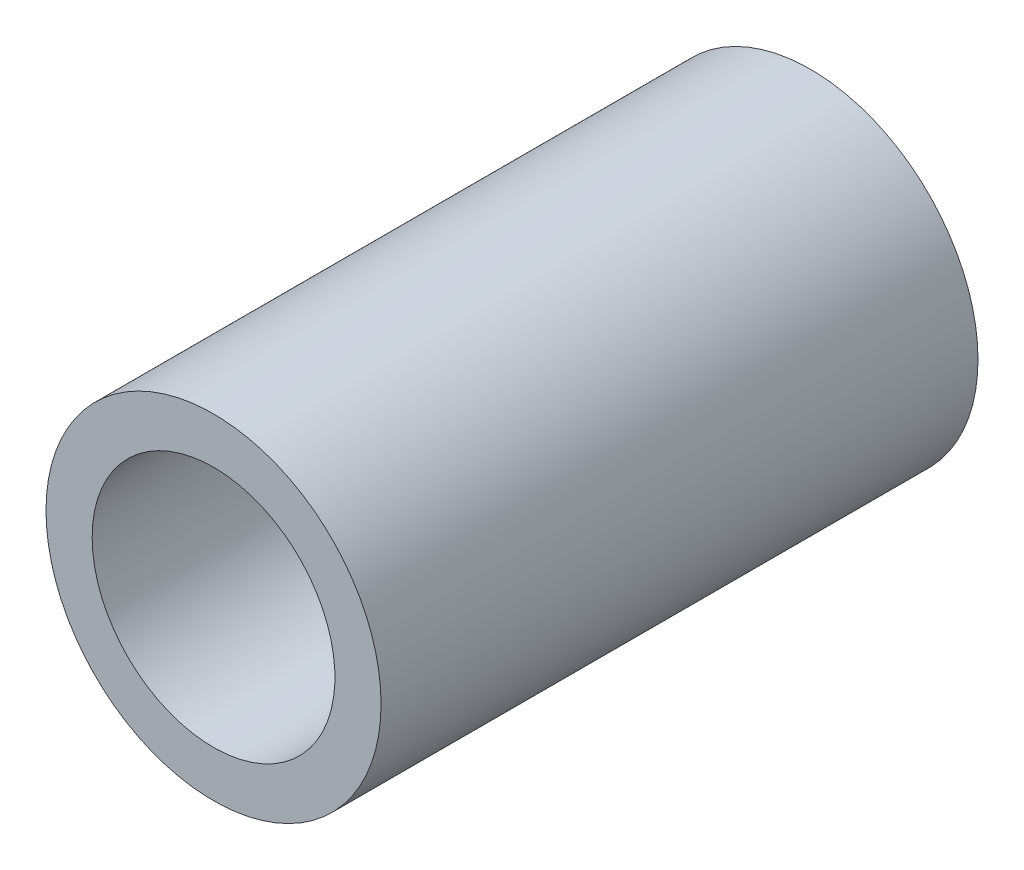
SolidWorks part; units mm, degrees
ref_plane "Front Plane" through (0, 0, 0) normal (0, 0, 1) x (1, 0, 0)
ref_plane "Top Plane" through (0, 0, 0) normal (0, 1, 0) x (1, 0, 0)
ref_plane "Right Plane" through (0, 0, 0) normal (1, 0, 0) x (0, 0, -1)
sketch "Sketch1" plane through (0, 0, 0) normal (0, 0, 1) x (1, 0, 0)
  circle A0 centre (0, 0) radius 10.6934
  circle A1 centre (0, 0) radius 7.747
  dimension "D1" = 21.3868
  dimension "D2" = 15.494
extrude "Boss-Extrude1" add sketch "Sketch1" along normal blind 38.1
